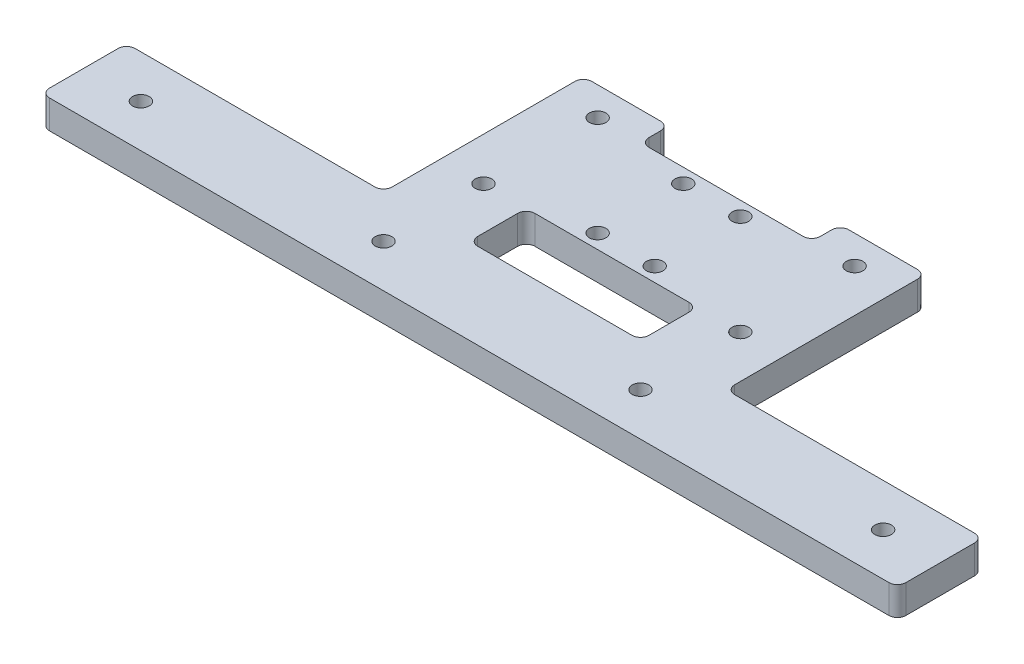
SolidWorks part; units mm, degrees
material "Thornel Mat VMA"
ref_plane "前视基准面" through (0, 0, 0) normal (0, 0, 1) x (1, 0, 0)
ref_plane "上视基准面" through (0, 0, 0) normal (0, 1, 0) x (1, 0, 0)
ref_plane "右视基准面" through (0, 0, 0) normal (1, 0, 0) x (0, 0, -1)
other "Configuration Table"
sketch "草图1" plane through (0, 0, 0) normal (0, 1, 0) x (1, 0, 0)
  line L1 (-15, -10) -> (15, -10)
  line L2 (-15, -10) -> (-15, 10)
  line L3 (-15, 10) -> (15, 10)
  line L4 (15, -10) -> (15, 10)
  line L5 (-15, -10) -> (15, 10) construction
  line L6 (-15, 10) -> (15, -10) construction
  point P0 (0, 0)
  dimension "D1" = 20
  dimension "D2" = 30
extrude "凸台-拉伸1" add sketch "草图1" along normal blind 5
sketch "草图2" plane through (0, 5, 0) normal (0, 1, 0) x (1, 0, 0)
  line L1 (-5, -7.5) -> (5, -7.5) construction
  line L2 (-5, -7.5) -> (-5, 7.5) construction
  line L3 (-5, 7.5) -> (5, 7.5) construction
  line L4 (5, -7.5) -> (5, 7.5) construction
  line L5 (-5, -7.5) -> (5, 7.5) construction
  line L6 (-5, 7.5) -> (5, -7.5) construction
  circle A0 centre (-5, 7.5) radius 1.45
  circle A1 centre (5, 7.5) radius 1.45
  circle A2 centre (5, -7.5) radius 1.45
  circle A3 centre (-5, -7.5) radius 1.45
  point P0 (0, 0)
  dimension "D3" = 2.9
  dimension "D4" = 2.9
  dimension "D5" = 2.9
  dimension "D6" = 2.9
  dimension "D1" = 15
  dimension "D2" = 10
extrude "切除-拉伸1" cut sketch "草图2" against normal through all
sketch "草图3" plane through (0, 5, 0) normal (0, 1, 0) x (1, 0, 0)
  line L0 (-22.5, 15) -> (-22.5, -15) construction
  line L1 (15, 15) -> (30, 15)
  line L2 (15, 15) -> (15, -15)
  line L3 (15, -15) -> (30, -15)
  line L4 (30, 15) -> (30, -15)
  line L5 (-15, 15) -> (-30, 15)
  line L6 (-15, 15) -> (-15, -15)
  line L7 (-15, -15) -> (-30, -15)
  line L8 (-30, 15) -> (-30, -15)
  line L9 (22.5, 15) -> (22.5, -15) construction
  line L10 (0, 0) -> (0, -10) construction
  line L11 (-15, -10) -> (15, -10) construction
  line L12 (-30, 0) -> (-15, 0) construction
  line L13 (-15, 10) -> (-15, -10) construction
  line L14 (15, -10) -> (15, 10) construction
  line L15 (30, 0) -> (15, 0) construction
  circle A0 centre (-22.5, 10) radius 1.45
  circle A1 centre (-22.5, -10) radius 1.45
  circle A2 centre (22.5, -10) radius 1.45
  circle A3 centre (22.5, 10) radius 1.45
  dimension "D5" = 2.9
  dimension "D6" = 2.9
  dimension "D7" = 5
  dimension "D8" = 5
  dimension "D1" = 30
  dimension "D2" = 15
  dimension "D3" = 30
  dimension "D4" = 15
extrude "凸台-拉伸2" add sketch "草图3" against normal blind 5
sketch "草图6" plane through (0, 5, 0) normal (0, 1, 0) x (1, 0, 0)
  line L0 (-15, -15) -> (-15, -10) construction
  line L1 (-30, -15) -> (-15, -15)
  line L2 (-30, -15) -> (-30, -20)
  line L3 (-30, -20) -> (-15, -20)
  line L4 (-15, -15) -> (-15, -20)
  line L5 (15, -15) -> (30, -15)
  line L6 (15, -15) -> (15, -20)
  line L7 (15, -20) -> (30, -20)
  line L8 (30, -15) -> (30, -20)
  dimension "D1" = 5
  dimension "D2" = 15
extrude "凸台-拉伸4" add sketch "草图6" against normal up to surface (5 mm away) up to face at (-5, 0, 8.95)
sketch "草图4" plane through (0, 5, 0) normal (0, 1, 0) x (1, 0, 0)
  line L0 (0, 0) -> (0, -20) construction
  line L1 (-75, -20) -> (75, -20)
  line L2 (-75, -20) -> (-75, -35)
  line L3 (-75, -35) -> (75, -35)
  line L4 (75, -20) -> (75, -35)
  line L6 (-75, -27.5) -> (75, -27.5) construction
  line L7 (22.5, 15) -> (22.5, -35) construction
  line L8 (30, 15) -> (15, 15) construction
  line L9 (-75, -20) -> (-75, -35)
  line L10 (75, -20) -> (75, -35)
  line L11 (15, -20) -> (30, -20) construction
  circle A0 centre (22.5, -27.5) radius 1.45
  circle A2 centre (-22.5, -27.5) radius 1.45
  circle A3 centre (65, -27.5) radius 1.45
  circle A4 centre (-65, -27.5) radius 1.45
  dimension "D2" = 2.9
  dimension "D3" = 2.9
  dimension "D5" = 10
  dimension "D1" = 15
  dimension "D4" = 150
extrude "凸台-拉伸3" add sketch "草图4" against normal up to surface (5 mm away)
fillet "圆角2" radius 1.5 16 edges at (-30, 2.5, -15) (-15, 2.5, -15) (15, 2.5, -10) (15, 2.5, -15) (30, 2.5, -15) (30, 2.5, 20) (75, 2.5, 20) (75, 2.5, 35) (-75, 2.5, 35) (-75, 2.5, 20) (-30, 2.5, 20) (-15, 2.5, -10) (15, 2.5, 20) (15, 2.5, 10) (-15, 2.5, 20) (-15, 2.5, 10)
